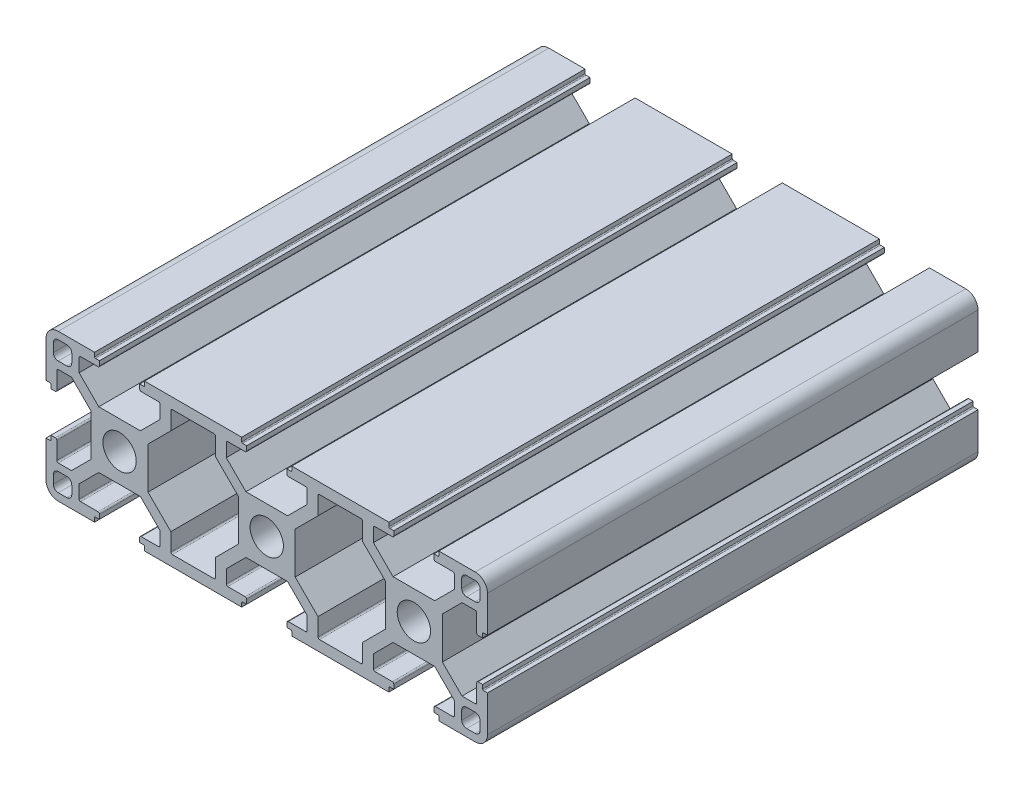
SolidWorks part; units mm, degrees
ref_plane "前视基准面" through (0, 0, 0) normal (0, 0, 1) x (1, 0, 0)
ref_plane "上视基准面" through (0, 0, 0) normal (0, 1, 0) x (1, 0, 0)
ref_plane "右视基准面" through (0, 0, 0) normal (1, 0, 0) x (0, 0, -1)
sketch "草图1" plane through (0, 0, 0) normal (0, 0, 1) x (1, 0, 0)
  line L0 (-51.1438, -7.9287) -> (-51.1438, -9.6787)
  line L1 (-52.1438, -10.6787) -> (-53.8938, -10.6787)
  line L2 (-54.8938, -9.6787) -> (-54.8938, -7.9287)
  line L3 (-53.8938, -6.9287) -> (-52.1438, -6.9287)
  line L4 (-52.1438, 12.5713) -> (-53.8938, 12.5713)
  line L5 (-54.8938, 13.5713) -> (-54.8938, 15.3213)
  line L6 (-53.8938, 16.3213) -> (-52.1438, 16.3213)
  line L7 (-51.1438, 15.3213) -> (-51.1438, 13.5713)
  line L8 (-30.9438, -6.0731) -> (-35.5938, -1.4231)
  line L9 (-35.5938, -1.4231) -> (-35.5938, 7.0656)
  line L10 (-35.5938, 7.0656) -> (-30.9438, 11.7156)
  line L11 (-28.8938, 17.8213) -> (-36.2938, 17.8213)
  line L12 (-36.2938, 17.8213) -> (-36.2938, 17.0213)
  line L13 (-36.4938, 16.8213) -> (-37.2938, 16.8213)
  line L14 (-37.2938, 16.8213) -> (-37.2938, 15.9213)
  line L15 (-36.9938, 15.6213) -> (-33.4438, 15.6213)
  line L16 (-33.1438, 15.3213) -> (-33.1438, 12.6269)
  line L17 (-33.1438, 12.6269) -> (-37.1494, 8.6213)
  line L18 (-37.1494, 8.6213) -> (-45.6381, 8.6213)
  line L19 (-45.6381, 8.6213) -> (-49.6438, 12.6269)
  line L20 (-49.6438, 12.6269) -> (-49.6438, 15.3213)
  line L21 (-49.3438, 15.6213) -> (-45.7938, 15.6213)
  line L22 (-45.4938, 15.9213) -> (-45.4938, 16.8213)
  line L23 (-45.4938, 16.8213) -> (-46.2938, 16.8213)
  line L24 (-46.4938, 17.0213) -> (-46.4938, 17.8213)
  line L25 (-46.4938, 17.8213) -> (-53.8938, 17.8213)
  line L26 (-56.3938, 15.3213) -> (-56.3938, 7.9213)
  line L27 (-56.3938, 7.9213) -> (-55.5938, 7.9213)
  line L28 (-55.3938, 7.7213) -> (-55.3938, 6.9213)
  line L29 (-55.3938, 6.9213) -> (-54.4938, 6.9213)
  line L30 (-54.1938, 7.2213) -> (-54.1938, 10.7713)
  line L31 (-53.8938, 11.0713) -> (-51.1994, 11.0713)
  line L32 (-51.1994, 11.0713) -> (-47.1938, 7.0656)
  line L33 (-47.1938, 7.0656) -> (-47.1938, -1.4231)
  line L34 (-47.1938, -1.4231) -> (-51.1994, -5.4287)
  line L35 (-51.1994, -5.4287) -> (-53.8938, -5.4287)
  line L36 (-54.1938, -5.1287) -> (-54.1938, -1.5787)
  line L37 (-54.4938, -1.2787) -> (-55.3938, -1.2787)
  line L38 (-55.3938, -1.2787) -> (-55.3938, -2.0787)
  line L39 (-55.5938, -2.2787) -> (-56.3938, -2.2787)
  line L40 (-56.3938, -2.2787) -> (-56.3938, -9.6787)
  line L41 (-53.8938, -12.1787) -> (-46.4938, -12.1787)
  line L42 (-46.4938, -12.1787) -> (-46.4938, -11.3787)
  line L43 (-46.2938, -11.1787) -> (-45.4938, -11.1787)
  line L44 (-45.4938, -11.1787) -> (-45.4938, -10.2787)
  line L45 (-45.7938, -9.9787) -> (-49.3438, -9.9787)
  line L46 (-49.6438, -9.6787) -> (-49.6438, -6.9844)
  line L47 (-49.6438, -6.9844) -> (-45.6381, -2.9787)
  line L48 (-45.6381, -2.9787) -> (-37.1494, -2.9787)
  line L49 (-37.1494, -2.9787) -> (-33.1438, -6.9844)
  line L50 (-33.1438, -6.9844) -> (-33.1438, -9.6787)
  line L51 (-33.4438, -9.9787) -> (-36.9938, -9.9787)
  line L52 (-37.2938, -10.2787) -> (-37.2938, -11.1787)
  line L53 (-37.2938, -11.1787) -> (-36.4938, -11.1787)
  line L54 (-36.2938, -11.3787) -> (-36.2938, -12.1787)
  line L55 (-36.2938, -12.1787) -> (-28.8938, -12.1787)
  line L56 (-23.8938, -12.1787) -> (-16.4938, -12.1787)
  line L57 (-16.4938, -12.1787) -> (-16.4938, -11.3787)
  line L58 (-16.2938, -11.1787) -> (-15.4938, -11.1787)
  line L59 (-15.4938, -11.1787) -> (-15.4938, -10.2787)
  line L60 (-15.7938, -9.9787) -> (-19.3438, -9.9787)
  line L61 (-19.6438, -9.6787) -> (-19.6438, -6.9844)
  line L62 (-19.6438, -6.9844) -> (-15.6381, -2.9787)
  line L63 (-15.6381, -2.9787) -> (-7.1494, -2.9787)
  line L64 (-7.1494, -2.9787) -> (-3.1438, -6.9844)
  line L65 (-3.1438, -6.9844) -> (-3.1438, -9.6787)
  line L66 (-3.4438, -9.9787) -> (-6.9938, -9.9787)
  line L67 (-7.2938, -10.2787) -> (-7.2938, -11.1787)
  line L68 (-7.2938, -11.1787) -> (-6.4938, -11.1787)
  line L69 (-6.2938, -11.3787) -> (-6.2938, -12.1787)
  line L72 (-5.5938, -1.4231) -> (-5.5938, 7.0656)
  line L75 (-6.2938, 17.8213) -> (-6.2938, 17.0213)
  line L76 (-6.4938, 16.8213) -> (-7.2938, 16.8213)
  line L77 (-7.2938, 16.8213) -> (-7.2938, 15.9213)
  line L78 (-6.9938, 15.6213) -> (-3.4438, 15.6213)
  line L79 (-3.1438, 15.3213) -> (-3.1438, 12.6269)
  line L80 (-3.1438, 12.6269) -> (-7.1494, 8.6213)
  line L81 (-7.1494, 8.6213) -> (-15.6381, 8.6213)
  line L82 (-15.6381, 8.6213) -> (-19.6438, 12.6269)
  line L83 (-19.6438, 12.6269) -> (-19.6438, 15.3213)
  line L84 (-19.3438, 15.6213) -> (-15.7938, 15.6213)
  line L85 (-15.4938, 15.9213) -> (-15.4938, 16.8213)
  line L86 (-15.4938, 16.8213) -> (-16.2938, 16.8213)
  line L87 (-16.4938, 17.0213) -> (-16.4938, 17.8213)
  line L88 (-16.4938, 17.8213) -> (-23.8938, 17.8213)
  line L89 (-21.8438, 11.7156) -> (-17.1938, 7.0656)
  line L90 (-17.1938, 7.0656) -> (-17.1938, -1.4231)
  line L91 (-17.1938, -1.4231) -> (-21.8438, -6.0731)
  line L92 (-28.8938, 17.8213) -> (-23.8938, 17.8213)
  line L93 (-28.8938, -12.1787) -> (-23.8938, -12.1787)
  line L94 (-21.8438, -9.6787) -> (-21.8438, -6.0731)
  line L95 (-30.9438, -9.6787) -> (-30.9438, -6.0731)
  line L97 (-30.6438, -9.9787) -> (-22.1438, -9.9787)
  line L99 (-30.6438, 15.6213) -> (-22.1438, 15.6213)
  line L100 (-30.9438, 15.3213) -> (-30.9438, 11.7156)
  line L101 (-21.8438, 15.3213) -> (-21.8438, 11.7156)
  line L122 (13.5062, 17.8213) -> (-6.2938, 17.8213)
  line L203 (29.3562, -6.9287) -> (31.1062, -6.9287)
  line L204 (32.1062, -7.9287) -> (32.1062, -9.6787)
  line L205 (31.1062, -10.6787) -> (29.3562, -10.6787)
  line L206 (28.3562, -9.6787) -> (28.3562, -7.9287)
  line L207 (28.3562, 13.5713) -> (28.3562, 15.3213)
  line L208 (29.3562, 16.3213) -> (31.1062, 16.3213)
  line L209 (32.1062, 15.3213) -> (32.1062, 13.5713)
  line L210 (31.1062, 12.5713) -> (29.3562, 12.5713)
  line L212 (12.8062, 7.0656) -> (12.8062, -1.4231)
  line L215 (13.5062, -12.1787) -> (13.5062, -11.3787)
  line L216 (13.7062, -11.1787) -> (14.5062, -11.1787)
  line L217 (14.5062, -11.1787) -> (14.5062, -10.2787)
  line L218 (14.2062, -9.9787) -> (10.6562, -9.9787)
  line L219 (10.3562, -9.6787) -> (10.3562, -6.9844)
  line L220 (10.3562, -6.9844) -> (14.3619, -2.9787)
  line L221 (14.3619, -2.9787) -> (22.8506, -2.9787)
  line L222 (22.8506, -2.9787) -> (26.8562, -6.9844)
  line L223 (26.8562, -6.9844) -> (26.8562, -9.6787)
  line L224 (26.5562, -9.9787) -> (23.0062, -9.9787)
  line L225 (22.7062, -10.2787) -> (22.7062, -11.1787)
  line L226 (22.7062, -11.1787) -> (23.5062, -11.1787)
  line L227 (23.7062, -11.3787) -> (23.7062, -12.1787)
  line L228 (23.7062, -12.1787) -> (31.1062, -12.1787)
  line L229 (33.6062, -9.6787) -> (33.6062, -2.2787)
  line L230 (33.6062, -2.2787) -> (32.8062, -2.2787)
  line L231 (32.6062, -2.0787) -> (32.6062, -1.2787)
  line L232 (32.6062, -1.2787) -> (31.7062, -1.2787)
  line L233 (31.4062, -1.5787) -> (31.4062, -5.1287)
  line L234 (31.1062, -5.4287) -> (28.4119, -5.4287)
  line L235 (28.4119, -5.4287) -> (24.4062, -1.4231)
  line L236 (24.4062, -1.4231) -> (24.4062, 7.0656)
  line L237 (24.4062, 7.0656) -> (28.4119, 11.0713)
  line L238 (28.4119, 11.0713) -> (31.1062, 11.0713)
  line L239 (31.4062, 10.7713) -> (31.4062, 7.2213)
  line L240 (31.7062, 6.9213) -> (32.6062, 6.9213)
  line L241 (32.6062, 6.9213) -> (32.6062, 7.7213)
  line L242 (32.8062, 7.9213) -> (33.6062, 7.9213)
  line L243 (33.6062, 7.9213) -> (33.6062, 15.3213)
  line L244 (31.1062, 17.8213) -> (23.7062, 17.8213)
  line L245 (23.7062, 17.8213) -> (23.7062, 17.0213)
  line L246 (23.5062, 16.8213) -> (22.7062, 16.8213)
  line L247 (22.7062, 16.8213) -> (22.7062, 15.9213)
  line L248 (23.0062, 15.6213) -> (26.5562, 15.6213)
  line L249 (26.8562, 15.3213) -> (26.8562, 12.6269)
  line L250 (26.8562, 12.6269) -> (22.8506, 8.6213)
  line L251 (22.8506, 8.6213) -> (14.3619, 8.6213)
  line L252 (14.3619, 8.6213) -> (10.3562, 12.6269)
  line L253 (10.3562, 12.6269) -> (10.3562, 15.3213)
  line L254 (10.6562, 15.6213) -> (14.2062, 15.6213)
  line L255 (14.5062, 15.9213) -> (14.5062, 16.8213)
  line L256 (14.5062, 16.8213) -> (13.7062, 16.8213)
  line L257 (13.5062, 17.0213) -> (13.5062, 17.8213)
  line L260 (-0.9438, 11.7156) -> (-0.9438, 15.3213)
  line L261 (-0.6438, 15.6213) -> (7.8562, 15.6213)
  line L262 (8.1562, 15.3213) -> (8.1562, 11.7156)
  line L263 (8.1562, 11.7156) -> (12.8062, 7.0656)
  line L266 (8.1562, -6.0731) -> (8.1562, -9.6787)
  line L267 (7.8562, -9.9787) -> (-0.6438, -9.9787)
  line L268 (-0.9438, -9.6787) -> (-0.9438, -6.0731)
  line L269 (-0.9438, -6.0731) -> (-5.5938, -1.4231)
  line L279 (-5.5938, 7.0656) -> (-0.9438, 11.7156)
  line L285 (12.8062, -1.4231) -> (8.1562, -6.0731)
  line L363 (-6.2938, -12.1787) -> (13.5062, -12.1787)
  arc A0 (-52.1438, -10.6787) -> (-51.1438, -9.6787) centre (-52.1438, -9.6787) ccw
  arc A1 (-54.8938, -9.6787) -> (-53.8938, -10.6787) centre (-53.8938, -9.6787) ccw
  arc A2 (-53.8938, -6.9287) -> (-54.8938, -7.9287) centre (-53.8938, -7.9287) ccw
  arc A3 (-51.1438, -7.9287) -> (-52.1438, -6.9287) centre (-52.1438, -7.9287) ccw
  arc A4 (-54.8938, 13.5713) -> (-53.8938, 12.5713) centre (-53.8938, 13.5713) ccw
  arc A5 (-53.8938, 16.3213) -> (-54.8938, 15.3213) centre (-53.8938, 15.3213) ccw
  arc A6 (-51.1438, 15.3213) -> (-52.1438, 16.3213) centre (-52.1438, 15.3213) ccw
  arc A7 (-52.1438, 12.5713) -> (-51.1438, 13.5713) centre (-52.1438, 13.5713) ccw
  arc A9 (-36.4938, 16.8213) -> (-36.2938, 17.0213) centre (-36.4938, 17.0213) ccw
  arc A10 (-37.2938, 15.9213) -> (-36.9938, 15.6213) centre (-36.9938, 15.9213) ccw
  arc A11 (-33.1438, 15.3213) -> (-33.4438, 15.6213) centre (-33.4438, 15.3213) ccw
  arc A12 (-49.3438, 15.6213) -> (-49.6438, 15.3213) centre (-49.3438, 15.3213) ccw
  arc A13 (-45.7938, 15.6213) -> (-45.4938, 15.9213) centre (-45.7938, 15.9213) ccw
  arc A14 (-46.4938, 17.0213) -> (-46.2938, 16.8213) centre (-46.2938, 17.0213) ccw
  arc A15 (-53.8938, 17.8213) -> (-56.3938, 15.3213) centre (-53.8938, 15.3213) ccw
  arc A16 (-55.3938, 7.7213) -> (-55.5938, 7.9213) centre (-55.5938, 7.7213) ccw
  arc A17 (-54.4938, 6.9213) -> (-54.1938, 7.2213) centre (-54.4938, 7.2213) ccw
  arc A18 (-53.8938, 11.0713) -> (-54.1938, 10.7713) centre (-53.8938, 10.7713) ccw
  arc A19 (-54.1938, -5.1287) -> (-53.8938, -5.4287) centre (-53.8938, -5.1287) ccw
  arc A20 (-54.1938, -1.5787) -> (-54.4938, -1.2787) centre (-54.4938, -1.5787) ccw
  arc A21 (-55.5938, -2.2787) -> (-55.3938, -2.0787) centre (-55.5938, -2.0787) ccw
  arc A22 (-56.3938, -9.6787) -> (-53.8938, -12.1787) centre (-53.8938, -9.6787) ccw
  arc A23 (-46.2938, -11.1787) -> (-46.4938, -11.3787) centre (-46.2938, -11.3787) ccw
  arc A24 (-45.4938, -10.2787) -> (-45.7938, -9.9787) centre (-45.7938, -10.2787) ccw
  arc A25 (-49.6438, -9.6787) -> (-49.3438, -9.9787) centre (-49.3438, -9.6787) ccw
  arc A26 (-33.4438, -9.9787) -> (-33.1438, -9.6787) centre (-33.4438, -9.6787) ccw
  arc A27 (-36.9938, -9.9787) -> (-37.2938, -10.2787) centre (-36.9938, -10.2787) ccw
  arc A28 (-36.2938, -11.3787) -> (-36.4938, -11.1787) centre (-36.4938, -11.3787) ccw
  arc A30 (-16.2938, -11.1787) -> (-16.4938, -11.3787) centre (-16.2938, -11.3787) ccw
  arc A31 (-15.4938, -10.2787) -> (-15.7938, -9.9787) centre (-15.7938, -10.2787) ccw
  arc A32 (-19.6438, -9.6787) -> (-19.3438, -9.9787) centre (-19.3438, -9.6787) ccw
  arc A33 (-3.4438, -9.9787) -> (-3.1438, -9.6787) centre (-3.4438, -9.6787) ccw
  arc A34 (-6.9938, -9.9787) -> (-7.2938, -10.2787) centre (-6.9938, -10.2787) ccw
  arc A35 (-6.2938, -11.3787) -> (-6.4938, -11.1787) centre (-6.4938, -11.3787) ccw
  arc A36 (-6.4938, 16.8213) -> (-6.2938, 17.0213) centre (-6.4938, 17.0213) ccw
  arc A37 (-7.2938, 15.9213) -> (-6.9938, 15.6213) centre (-6.9938, 15.9213) ccw
  arc A38 (-3.1438, 15.3213) -> (-3.4438, 15.6213) centre (-3.4438, 15.3213) ccw
  arc A39 (-19.3438, 15.6213) -> (-19.6438, 15.3213) centre (-19.3438, 15.3213) ccw
  arc A40 (-15.7938, 15.6213) -> (-15.4938, 15.9213) centre (-15.7938, 15.9213) ccw
  arc A41 (-16.4938, 17.0213) -> (-16.2938, 16.8213) centre (-16.2938, 17.0213) ccw
  arc A42 (-30.9438, -9.6787) -> (-30.6438, -9.9787) centre (-30.6438, -9.6787) ccw
  arc A43 (-22.1438, -9.9787) -> (-21.8438, -9.6787) centre (-22.1438, -9.6787) ccw
  arc A44 (-30.6438, 15.6213) -> (-30.9438, 15.3213) centre (-30.6438, 15.3213) ccw
  arc A45 (-21.8438, 15.3213) -> (-22.1438, 15.6213) centre (-22.1438, 15.3213) ccw
  arc A92 (32.1062, -7.9287) -> (31.1062, -6.9287) centre (31.1062, -7.9287) ccw
  arc A93 (31.1062, -10.6787) -> (32.1062, -9.6787) centre (31.1062, -9.6787) ccw
  arc A94 (28.3562, -9.6787) -> (29.3562, -10.6787) centre (29.3562, -9.6787) ccw
  arc A95 (29.3562, -6.9287) -> (28.3562, -7.9287) centre (29.3562, -7.9287) ccw
  arc A96 (29.3562, 16.3213) -> (28.3562, 15.3213) centre (29.3562, 15.3213) ccw
  arc A97 (32.1062, 15.3213) -> (31.1062, 16.3213) centre (31.1062, 15.3213) ccw
  arc A98 (31.1062, 12.5713) -> (32.1062, 13.5713) centre (31.1062, 13.5713) ccw
  arc A99 (28.3562, 13.5713) -> (29.3562, 12.5713) centre (29.3562, 13.5713) ccw
  arc A101 (13.7062, -11.1787) -> (13.5062, -11.3787) centre (13.7062, -11.3787) ccw
  arc A102 (14.5062, -10.2787) -> (14.2062, -9.9787) centre (14.2062, -10.2787) ccw
  arc A103 (10.3562, -9.6787) -> (10.6562, -9.9787) centre (10.6562, -9.6787) ccw
  arc A104 (26.5562, -9.9787) -> (26.8562, -9.6787) centre (26.5562, -9.6787) ccw
  arc A105 (23.0062, -9.9787) -> (22.7062, -10.2787) centre (23.0062, -10.2787) ccw
  arc A106 (23.7062, -11.3787) -> (23.5062, -11.1787) centre (23.5062, -11.3787) ccw
  arc A107 (31.1062, -12.1787) -> (33.6062, -9.6787) centre (31.1062, -9.6787) ccw
  arc A108 (32.6062, -2.0787) -> (32.8062, -2.2787) centre (32.8062, -2.0787) ccw
  arc A109 (31.7062, -1.2787) -> (31.4062, -1.5787) centre (31.7062, -1.5787) ccw
  arc A110 (31.1062, -5.4287) -> (31.4062, -5.1287) centre (31.1062, -5.1287) ccw
  arc A111 (31.4062, 10.7713) -> (31.1062, 11.0713) centre (31.1062, 10.7713) ccw
  arc A112 (31.4062, 7.2213) -> (31.7062, 6.9213) centre (31.7062, 7.2213) ccw
  arc A113 (32.8062, 7.9213) -> (32.6062, 7.7213) centre (32.8062, 7.7213) ccw
  arc A114 (33.6062, 15.3213) -> (31.1062, 17.8213) centre (31.1062, 15.3213) ccw
  arc A115 (23.5062, 16.8213) -> (23.7062, 17.0213) centre (23.5062, 17.0213) ccw
  arc A116 (22.7062, 15.9213) -> (23.0062, 15.6213) centre (23.0062, 15.9213) ccw
  arc A117 (26.8562, 15.3213) -> (26.5562, 15.6213) centre (26.5562, 15.3213) ccw
  arc A118 (10.6562, 15.6213) -> (10.3562, 15.3213) centre (10.6562, 15.3213) ccw
  arc A119 (14.2062, 15.6213) -> (14.5062, 15.9213) centre (14.2062, 15.9213) ccw
  arc A120 (13.5062, 17.0213) -> (13.7062, 16.8213) centre (13.7062, 17.0213) ccw
  arc A121 (-0.6438, 15.6213) -> (-0.9438, 15.3213) centre (-0.6438, 15.3213) ccw
  arc A122 (8.1562, 15.3213) -> (7.8562, 15.6213) centre (7.8562, 15.3213) ccw
  arc A123 (7.8562, -9.9787) -> (8.1562, -9.6787) centre (7.8562, -9.6787) ccw
  arc A124 (-0.9438, -9.6787) -> (-0.6438, -9.9787) centre (-0.6438, -9.6787) ccw
  circle A133 centre (18.6062, 2.8213) radius 3.4
  circle A138 centre (-11.3938, 2.8213) radius 3.4
  circle A147 centre (-41.3938, 2.8213) radius 3.4
extrude "凸台-拉伸1" add sketch "草图1" along normal blind 100
